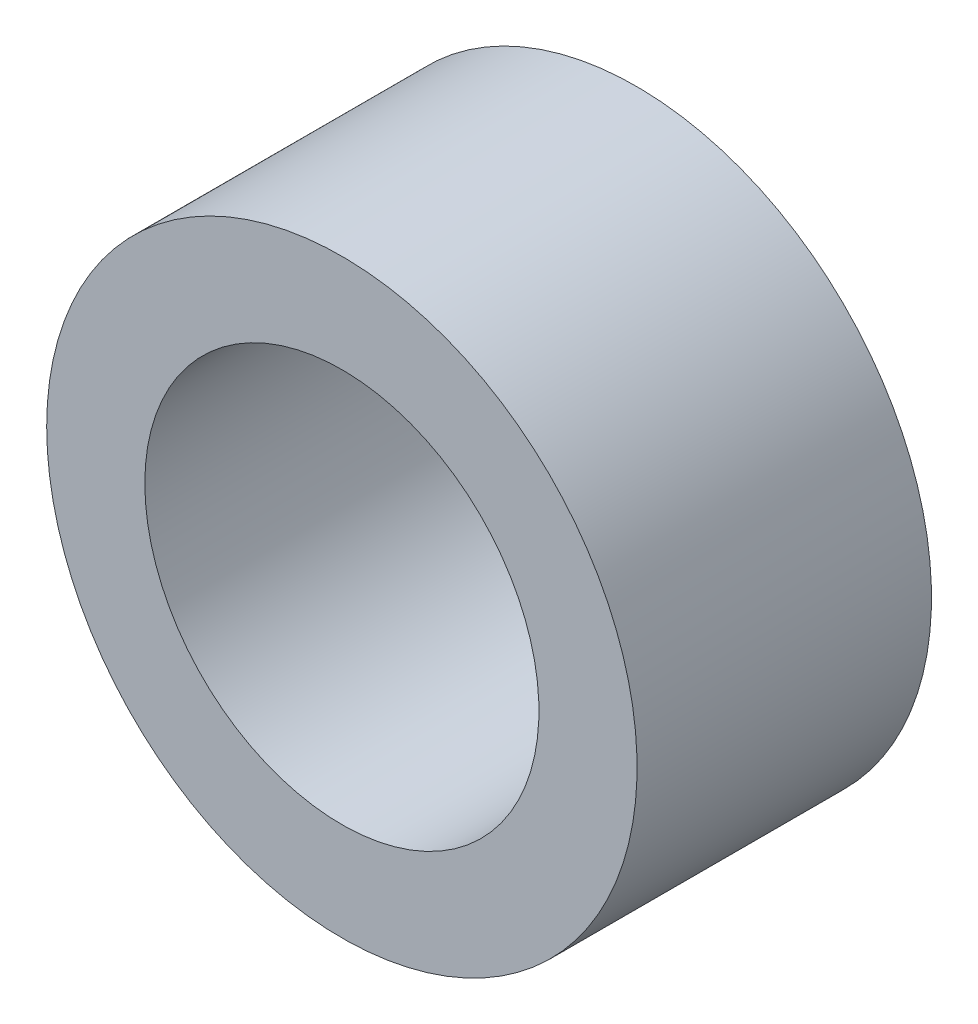
SolidWorks part; units mm, degrees
ref_plane "Front Plane" through (0, 0, 0) normal (0, 0, 1) x (1, 0, 0)
ref_plane "Top Plane" through (0, 0, 0) normal (0, 1, 0) x (1, 0, 0)
ref_plane "Right Plane" through (0, 0, 0) normal (1, 0, 0) x (0, 0, -1)
sketch "Sketch1" plane through (0, 0, 0) normal (0, 0, 1) x (1, 0, 0)
  circle A0 centre (0, 0) radius 9.5504
  circle A1 centre (0, 0) radius 6.3754
  dimension "D1" = 19.1008
  dimension "ID" = 12.7508
extrude "Extrude1" add sketch "Sketch1" along normal mid plane 9.525
sketch "Sketch2" plane through (0, 0, 0) normal (1, 0, 0) x (0, 0, -1)
  line L0 (-4.7625, -6.3754) -> (4.7625, -6.3754) construction
  line L3 (4.7625, 6.3754) -> (-4.7625, 6.3754) construction
  line L5 (-4.7625, -6.3754) -> (4.7625, -6.3754)
  line L6 (4.7625, 6.3754) -> (-4.7625, 6.3754)
sketch "Sketch4" plane through (0, 0, 4.7625) normal (0, 0, 1) x (1, 0, 0)
  line L0 (0, 0) -> (-4.5081, 4.5081)
  line L1 (0, -3.4925) -> (0, 3.4925) construction
  circle A0 centre (0, 0) radius 6.3754 construction
  dimension "D1" = 45
